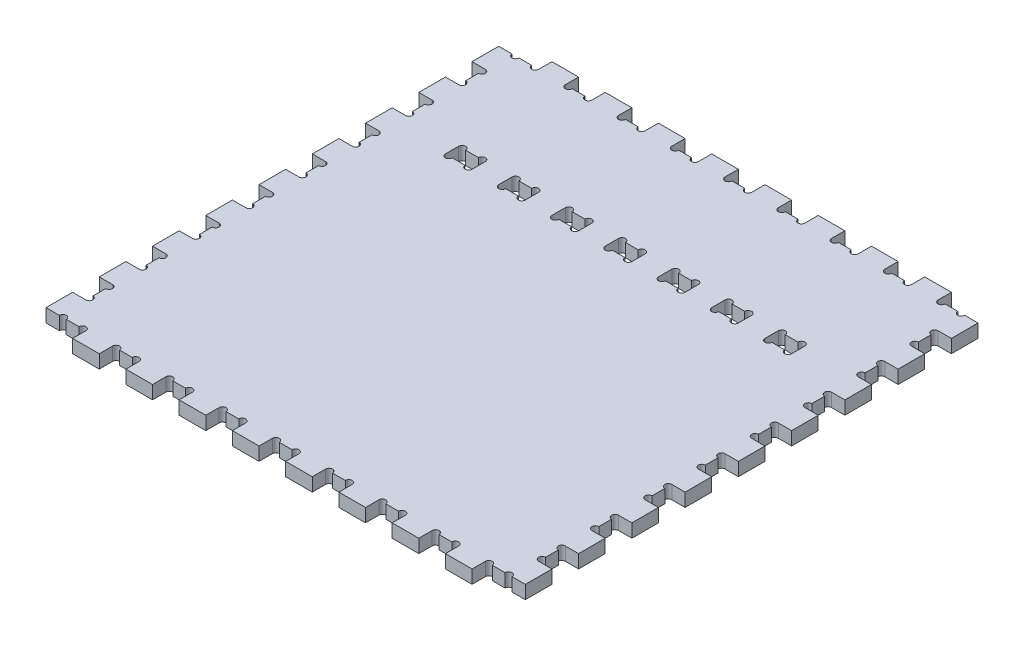
SolidWorks part; units mm, degrees
ref_plane "Front Plane" through (0, 0, 0) normal (0, 0, 1) x (1, 0, 0)
ref_plane "Top Plane" through (0, 0, 0) normal (0, 1, 0) x (1, 0, 0)
ref_plane "Right Plane" through (0, 0, 0) normal (1, 0, 0) x (0, 0, -1)
sketch "Sketch1" plane through (0, 0, 0) normal (0, 1, 0) x (1, 0, 0)
  line L1 (228.6, -228.6) -> (-228.6, -228.6)
  line L2 (228.6, -228.6) -> (228.6, 228.6)
  line L3 (228.6, 228.6) -> (-228.6, 228.6)
  line L4 (-228.6, -228.6) -> (-228.6, 228.6)
  line L5 (228.6, -228.6) -> (-228.6, 228.6) construction
  line L6 (228.6, 228.6) -> (-228.6, -228.6) construction
  point P0 (0, 0)
  dimension "D1" = 457.2
  dimension "D2" = 457.2
extrude "Boss-Extrude1" add sketch "Sketch1" along normal blind 12.7
sketch "Sketch2" plane through (0, 12.7, 0) normal (0, 1, 0) x (1, 0, 0)
  line L0 (228.6, 228.6) -> (-228.6, 228.6) construction
  line L1 (-215.9, 228.6) -> (-190.5, 228.6)
  line L2 (-215.9, 228.6) -> (-215.9, 215.9)
  line L3 (-215.9, 215.9) -> (-190.5, 215.9)
  line L4 (-190.5, 228.6) -> (-190.5, 215.9)
  line L5 (-215.9, 215.9) -> (-228.6, 215.9) construction
  line L6 (-228.6, 228.6) -> (-228.6, -228.6) construction
  circle A0 centre (-212.598, 215.9) radius 3.302
  circle A1 centre (-193.802, 215.9) radius 3.302
  line M8 (228.6, 228.6) -> (-228.6, 228.6)
  dimension "D3" = 6.604
  dimension "D4" = 6.604
  dimension "D1" = 25.4
  dimension "D2" = 12.7
  dimension "D5" = 12.7
extrude "Cut-Extrude1" cut sketch "Sketch2" against normal blind 12.7 contours A1 L4 L2 A0 L3 M8 | L3 A0 | L3 A1 | L3 A1 | L3 A0
pattern_linear "LPattern1" count 9 spacing 50.8 along (1, 0, 0) of "Cut-Extrude1"
ref_plane "Plane1" through (0, 0, 0) normal (0, 0, -1) x (-1, 0, 0)
ref_plane "Plane2" through (0, 0, 0) normal (-1, 0, 0) x (0, 0, 1)
mirror "Mirror1" about plane through (0, 0, 0) normal (0, 0, -1) of "LPattern1", "Cut-Extrude1"
sketch "Sketch3" plane through (0, 12.7, 0) normal (0, 1, 0) x (1, 0, 0)
  line L1 (-228.6, 228.6) -> (-215.9, 228.6)
  line L2 (-228.6, 228.6) -> (-228.6, 215.9)
  line L3 (-228.6, 215.9) -> (-215.9, 215.9)
  line L4 (-215.9, 228.6) -> (-215.9, 215.9)
extrude "Cut-Extrude2" cut sketch "Sketch3" against normal through all
mirror "Mirror2" about plane through (0, 0, 0) normal (-1, 0, 0) of "Cut-Extrude2"
mirror "Mirror3" about plane through (0, 0, 0) normal (0, 0, -1) of "Mirror2", "Cut-Extrude2"
sketch "Sketch4" plane through (0, 12.7, 0) normal (0, 1, 0) x (1, 0, 0)
  line L0 (-228.6, 215.9) -> (-228.6, -215.9) construction
  line L1 (-228.6, 190.5) -> (-215.9, 190.5)
  line L2 (-228.6, 190.5) -> (-228.6, 165.1)
  line L3 (-228.6, 165.1) -> (-215.9, 165.1)
  line L4 (-215.9, 190.5) -> (-215.9, 165.1)
  line L5 (-215.9, 190.5) -> (-186.3664, 190.5) construction
  line L6 (-186.3664, 190.5) -> (-186.3664, 228.6) construction
  line L7 (-165.1, 228.6) -> (-190.5, 228.6) construction
  circle A0 centre (-215.9, 187.198) radius 3.302
  circle A1 centre (-215.9, 168.402) radius 3.302
  dimension "D3" = 6.604
  dimension "D4" = 6.604
  dimension "D1" = 12.7
  dimension "D2" = 25.4
  dimension "D5" = 38.1
extrude "Cut-Extrude3" cut sketch "Sketch4" against normal through all contours A1 L4 A0 L1 L2 L3 | L4 A0 | L4 A1 | L4 A1 | L4 A0
pattern_linear "LPattern2" count 9 spacing 50.8 along (0, 0, 1) of "Cut-Extrude3"
mirror "Mirror4" about plane through (0, 0, 0) normal (-1, 0, 0) of "LPattern2", "Cut-Extrude3"
sketch "Sketch5" plane through (0, 12.7, 0) normal (0, 1, 0) x (1, 0, 0)
  line L1 (-165.1, 114.3) -> (-139.7, 114.3)
  line L2 (-165.1, 114.3) -> (-165.1, 101.6)
  line L3 (-165.1, 101.6) -> (-139.7, 101.6)
  line L4 (-139.7, 114.3) -> (-139.7, 101.6)
  line L6 (-165.1, 228.6) -> (-165.1, 114.3) construction
  line L8 (-165.1, 228.6) -> (-165.1, 215.9) construction
  line L9 (-165.1, 114.3) -> (-215.9, 114.3) construction
  line L10 (-228.6, 114.3) -> (-215.9, 114.3) construction
  circle A0 centre (-161.798, 114.3) radius 3.302
  circle A1 centre (-143.002, 114.3) radius 3.302
  circle A2 centre (-161.798, 101.6) radius 3.302
  circle A3 centre (-143.002, 101.6) radius 3.302
  arc A4 (-215.9, 114.3) -> (-215.9, 120.904) centre (-215.9, 117.602) ccw construction
  dimension "D3" = 6.604
  dimension "D1" = 12.7
  dimension "D2" = 25.4
  dimension "D4" = 114.3
extrude "Cut-Extrude4" cut sketch "Sketch5" against normal through all contours A3 L4 A1 L1 A0 L2 A2 L3 | L1 A0 | L1 A0 | L3 A2 | L3 A2 | L3 A3 | L3 A3
pattern_linear "LPattern3" count 7 spacing 50.8 along (1, 0, 0) of "Cut-Extrude4"
